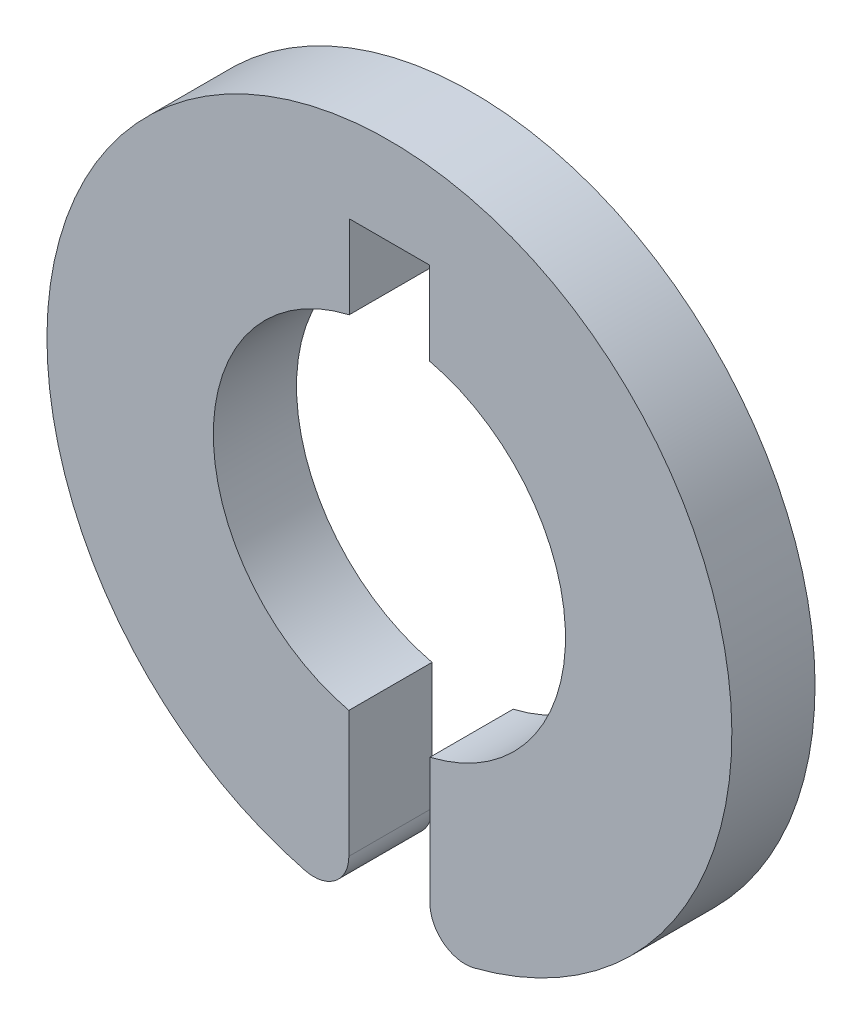
SolidWorks part; units mm, degrees
material "Acrylic (Medium-high impact)"
ref_plane "Front Plane" through (0, 0, 0) normal (0, 0, 1) x (1, 0, 0)
ref_plane "Top Plane" through (0, 0, 0) normal (0, 1, 0) x (1, 0, 0)
ref_plane "Right Plane" through (0, 0, 0) normal (1, 0, 0) x (0, 0, -1)
sketch "스케치1" plane through (0, 0, 0) normal (0, 0, 1) x (1, 0, 0)
  line L0 (0, 10.85) -> (0, 0) construction
  line L6 (-1.4475, 9.1828) -> (1.4475, 9.1828)
  line L7 (0, 0) -> (0, -9.2212) construction
  line L8 (-1.4625, -12.2631) -> (1.4625, -12.2631) construction
  line L9 (-1.4625, -12.2631) -> (-1.4625, -6.1793)
  line L10 (-1.4625, -6.1793) -> (1.4625, -6.1793) construction
  line L11 (1.4625, -12.2631) -> (1.4625, -6.1793)
  line L12 (-1.4625, -12.2631) -> (1.4625, -6.1793) construction
  line L13 (-1.4625, -6.1793) -> (1.4625, -12.2631) construction
  line L14 (-1.4475, 9.1828) -> (-1.4475, 6.1828)
  line L15 (-1.4475, 6.1828) -> (1.4475, 6.1828) construction
  line L16 (1.4475, 9.1828) -> (1.4475, 6.1828)
  line L17 (-1.4475, 9.1828) -> (1.4475, 6.1828) construction
  line L18 (-1.4475, 6.1828) -> (1.4475, 9.1828) construction
  circle A0 centre (0, 0) radius 12.35 construction
  circle A1 centre (0, 0) radius 6.35 construction
  arc A2 (-1.4625, -12.2631) -> (1.4625, -12.2631) centre (0, 0) cw
  arc A3 (1.4625, -6.1793) -> (1.4475, 6.1828) centre (0, 0) ccw
  arc A4 (-1.4475, 6.1828) -> (-1.4625, -6.1793) centre (0, 0) ccw
  point P2 (0, 10.85)
  point P5 (0, 7.6828)
  point P10 (0, -9.2212)
  dimension "D1" = 6
  dimension "D2" = 12.7
  dimension "D3" = 2.895
  dimension "D4" = 3
  dimension "D5" = 2.925
extrude "보스-돌출1" add sketch "스케치1" along normal blind 3
fillet "필렛1" radius 1.27 2 edges at (-1.4625, -12.2631, 1.5) (1.4625, -12.2631, 1.5)
